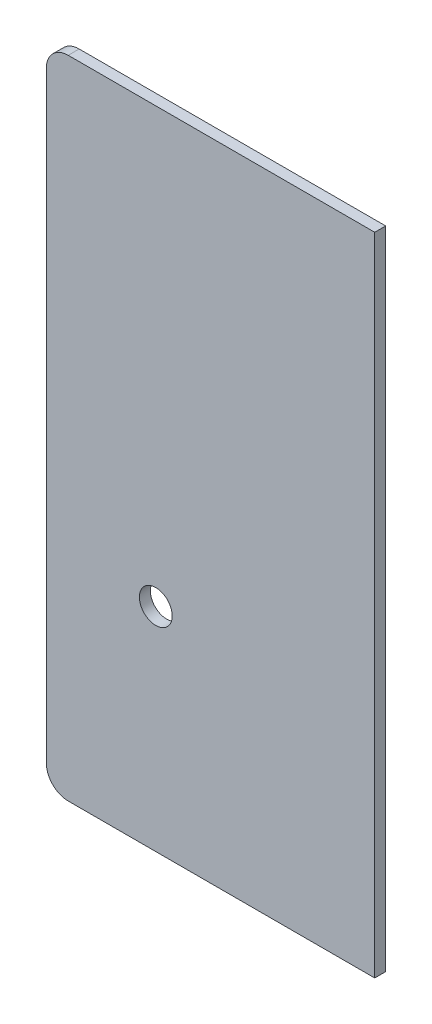
SolidWorks part; units mm, degrees
ref_plane "Front Plane" through (0, 0, 0) normal (0, 0, 1) x (1, 0, 0)
ref_plane "Top Plane" through (0, 0, 0) normal (0, 1, 0) x (1, 0, 0)
ref_plane "Right Plane" through (0, 0, 0) normal (1, 0, 0) x (0, 0, -1)
sketch "Sketch1" plane through (0, 0, 0) normal (0, 0, 1) x (1, 0, 0)
  line L0 (-44, 49.75) -> (-44, -9.25)
  line L5 (-74, 47.75) -> (-74, -7.25)
  line L10 (-72, 49.75) -> (-44, 49.75)
  line L11 (-72, -9.25) -> (-44, -9.25)
  arc A16 (-72, -9.25) -> (-74, -7.25) centre (-72, -7.25) cw
  arc A17 (-72, 49.75) -> (-74, 47.75) centre (-72, 47.75) ccw
  circle A23 centre (-64, 10.14) radius 1.5
  dimension "D6" = 10
  dimension "D7" = 30
  dimension "D8" = 19.39
  dimension "D42" = 3
  dimension "D1" = 44
  dimension "D2" = 9.25
  dimension "D3" = 55
  dimension "D5" = 28
extrude "Boss-Extrude1" add sketch "Sketch1" along normal blind 1
